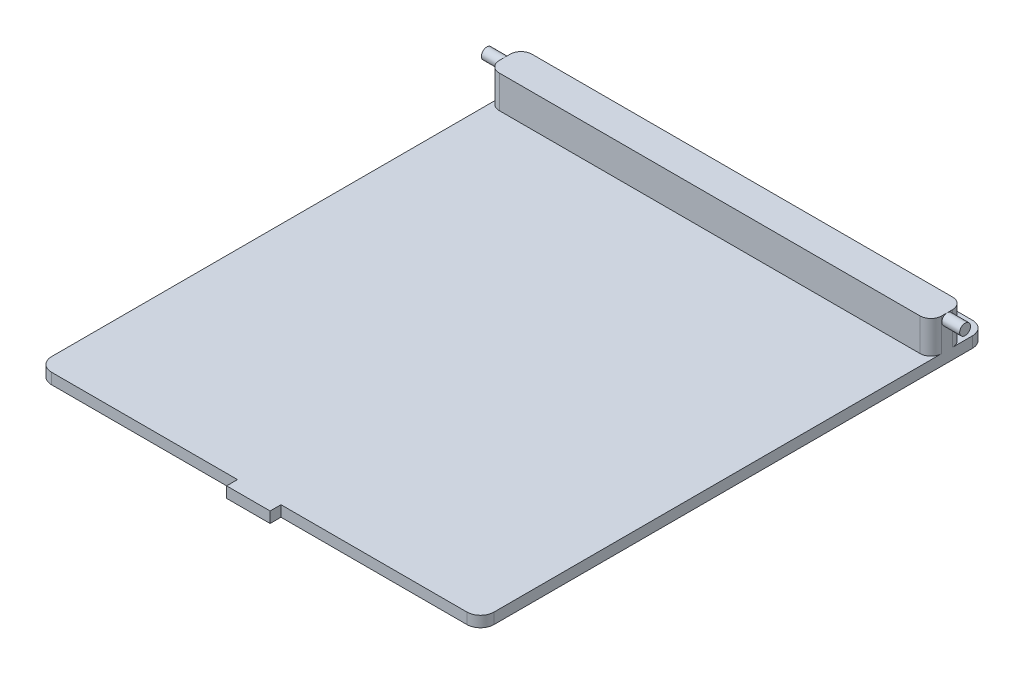
SolidWorks part; units mm, degrees
ref_plane "Front Plane" through (0, 0, 0) normal (0, 0, 1) x (1, 0, 0)
ref_plane "Top Plane" through (0, 0, 0) normal (0, 1, 0) x (1, 0, 0)
ref_plane "Right Plane" through (0, 0, 0) normal (1, 0, 0) x (0, 0, -1)
sketch "Sketch1" plane through (0, 0, 0) normal (0, 1, 0) x (1, 0, 0)
  line L1 (40.7, -3) -> (-40.7, -3)
  line L2 (40.7, -3) -> (40.7, 3)
  line L3 (40.7, 3) -> (-40.7, 3)
  line L4 (-40.7, -3) -> (-40.7, 3)
  line L5 (40.7, -3) -> (-40.7, 3) construction
  line L6 (40.7, 3) -> (-40.7, -3) construction
  point P0 (0, 0)
  dimension "D1" = 81.4
  dimension "D2" = 6
extrude "Boss-Extrude1" add sketch "Sketch1" along normal mid plane 6
fillet "Fillet1" radius 2 4 edges at (-40.7, 0, 3) (40.7, 0, 3) (40.7, 0, -3) (-40.7, 0, -3)
sketch "Sketch2" plane through (0, 0, 0) normal (1, 0, 0) x (0, 0, -1)
  line L2 (-1, 3) -> (1, 3) construction
  circle A0 centre (0, 2) radius 1
  point P2 (0, 2)
  point P4 (-1, 2)
  point P5 (1.9, 1.6959)
  dimension "D2" = 2
extrude "Boss-Extrude2" add sketch "Sketch2" along normal mid plane 88
sketch "Sketch3" plane through (0, -3, 0) normal (0, -1, 0) x (1, 0, 0)
  line L0 (40.7, -1) -> (40.7, 1) construction
  line L1 (-40.7, 85.86) -> (40.7, 85.86)
  line L2 (-40.7, 85.86) -> (-40.7, -7.14)
  line L3 (-40.7, -7.14) -> (40.7, -7.14)
  line L4 (40.7, 85.86) -> (40.7, -7.14)
  line L5 (-40.7, 85.86) -> (40.7, -7.14) construction
  line L6 (-40.7, -7.14) -> (40.7, 85.86) construction
  line L8 (-38.7, 3) -> (38.7, 3) construction
  point P0 (0, 39.36)
  point P5 (0, 0)
  dimension "D1" = 93
  dimension "D2" = 82.86
extrude "Boss-Extrude3" add sketch "Sketch3" along normal blind 2
fillet "Fillet2" radius 2.5 4 edges at (-40.7, -4, -7.14) (-40.7, -4, 85.86) (40.7, -4, 85.86) (40.7, -4, -7.14)
sketch "Sketch4" plane through (0, -5, 0) normal (0, -1, 0) x (1, 0, 0)
  line L0 (38.2, 85.86) -> (-38.2, 85.86) construction
  line L1 (-4, 83.86) -> (4, 83.86)
  line L2 (-4, 83.86) -> (-4, 87.86)
  line L3 (-4, 87.86) -> (4, 87.86)
  line L4 (4, 83.86) -> (4, 87.86)
  line L5 (-4, 83.86) -> (4, 87.86) construction
  line L6 (-4, 87.86) -> (4, 83.86) construction
  point P0 (0, 85.86)
  dimension "D1" = 2
  dimension "D2" = 8
extrude "Boss-Extrude4" add sketch "Sketch4" against normal up to surface (2 mm away) up to face at (0, -3, 43.538)
